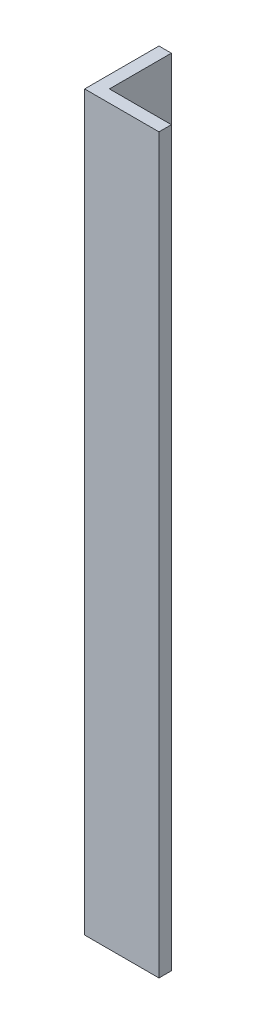
SolidWorks part; units mm, degrees
ref_plane "Alzado" through (0, 0, 0) normal (0, 0, 1) x (1, 0, 0)
ref_plane "Planta" through (0, 0, 0) normal (0, 1, 0) x (1, 0, 0)
ref_plane "Vista lateral" through (0, 0, 0) normal (1, 0, 0) x (0, 0, -1)
sketch "Croquis1" plane through (0, 0, 0) normal (0, 1, 0) x (1, 0, 0)
  line L0 (0, 0) -> (19.05, 0)
  line L1 (19.05, 0) -> (19.05, 3.175)
  line L2 (19.05, 3.175) -> (3.175, 3.175)
  line L3 (3.175, 3.175) -> (3.175, 19.05)
  line L4 (3.175, 19.05) -> (0, 19.05)
  line L5 (0, 19.05) -> (0, 0)
  dimension "D1" = 19.05
  dimension "D2" = 3.175
extrude "Saliente-Extruir1" add sketch "Croquis1" along normal mid plane 187.8026
